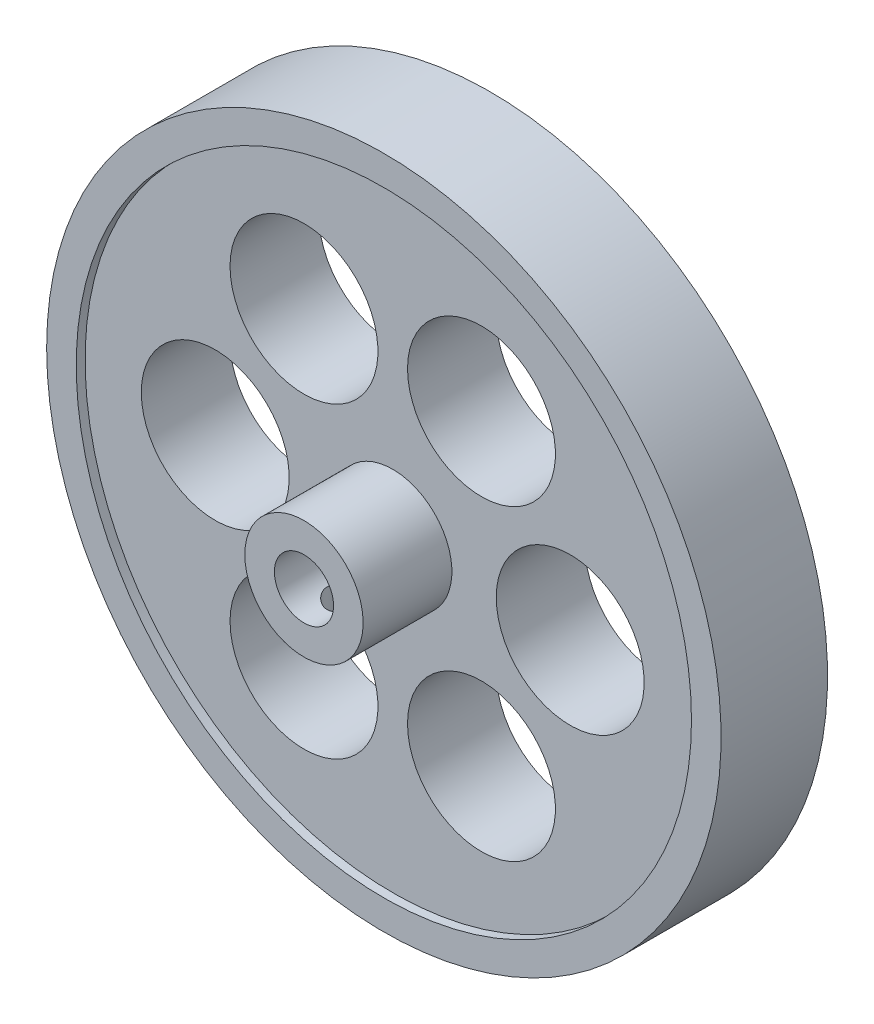
SolidWorks part; units mm, degrees
ref_plane "前视基准面" through (0, 0, 0) normal (0, 0, 1) x (1, 0, 0)
ref_plane "上视基准面" through (0, 0, 0) normal (0, 1, 0) x (1, 0, 0)
ref_plane "右视基准面" through (0, 0, 0) normal (1, 0, 0) x (0, 0, -1)
other "Configuration Table"
ref_plane "基准面1" through (0, 0, 0) normal (0, -1, 0) x (1, 0, 0)
sketch "草图1" plane through (0, 0, 0) normal (0, -1, 0) x (1, 0, 0)
  line L0 (57, 9) -> (0, 9)
  line L1 (0, 9) -> (0, -9)
  line L2 (0, -9) -> (57, -9)
  line L3 (57, -9) -> (57, 9)
  line L4 (0, 9) -> (0, -9) construction
revolve "旋转1" add sketch "草图1" angle 360 about L4
hole_wizard "M100 间隙孔1" positions "草图3" profile "草图2" hole size "M100" standard "ANSI Metric"
sketch "草图3" plane through (0, 0, 9) normal (0, 0, 1) x (1, 0, 0)
  point P0 (0, 0)
sketch "草图2" plane through (0, 0, 9) normal (1, 0, 0) x (0, -1, 0)
  line L0 (0, 0) -> (0, 1.5)
  line L1 (0, 1.5) -> (52, 1.5)
  line L2 (52, 1.5) -> (52, 0)
  line L5 (52, 0) -> (0, 0)
  line L10 (0, 1.5) -> (-52, 1.5) construction
  line L11 (0, -6.35) -> (0, 107.95) construction
  dimension "孔直径" = 104
  dimension "孔深度" = 1.5
  dimension "导头角度" = 180
sketch "草图4" plane through (0, 0, 0) normal (0, -1, 0) x (1, 0, 0)
  line L0 (10, 22.5) -> (0, 22.5)
  line L1 (0, 22.5) -> (0, 7.5)
  line L2 (0, 7.5) -> (10, 7.5)
  line L3 (10, 7.5) -> (10, 22.5)
  line L4 (0, 22.5) -> (0, 7.5) construction
revolve "旋转2" add sketch "草图4" angle 360 about L4
hole_wizard "M8 六角头螺栓的柱形沉头孔1" positions "草图6" profile "草图5" counterbore size "M8" standard "ANSI Metric"
sketch "草图6" plane through (0, 0, -9) normal (0, 0, -1) x (-1, 0, 0)
  point P0 (0, 0)
sketch "草图5" plane through (0, 0, -9) normal (1, 0, 0) x (0, 1, 0)
  line L0 (0, 0) -> (0, 31.5)
  line L1 (0, 31.5) -> (5, 31.5)
  line L3 (5, 31.5) -> (5, 1.5)
  line L4 (5, 1.5) -> (52, 1.5)
  line L5 (52, 1.5) -> (52, 0)
  line L7 (52, 0) -> (0, 0)
  line L11 (0, -6.35) -> (0, 107.95) construction
  dimension "通孔孔直径" = 10
  dimension "通孔孔深度" = 31.5
  dimension "柱形沉头孔直径" = 104
  dimension "柱形沉头孔深度" = 1.5
hole_wizard "Ø5.2 (5.2) 直径孔1" positions "3D草图1" profile "草图7" hole size "Ø5.2" standard "ANSI Metric"
sketch3d "3D草图1"
  point P0 (0, -10, 16)
sketch "草图7" plane through (0, -10, 16) normal (1, 0, 0) x (0, 0, -1)
  line L0 (0, 0) -> (0, 5)
  line L1 (0, 5) -> (2.6, 5)
  line L2 (2.6, 5) -> (2.6, 0)
  line L5 (2.6, 0) -> (0, 0)
  line L11 (0, -6.35) -> (0, 107.95) construction
  dimension "通孔孔直径" = 5.2
  dimension "通孔孔深度" = 5
hole_wizard "Ø25.0 (25) 直径孔1" positions "草图9" profile "草图8" hole size "Ø25.0" standard "ANSI Metric"
sketch "草图9" plane through (0, 0, -7.5) normal (0, 0, -1) x (-1, 0, 0)
  point P0 (-30, 0)
  point P1 (-15, 25.9808)
  point P2 (15, 25.9808)
  point P3 (30, 0)
  point P4 (15, -25.9808)
  point P5 (-15, -25.9808)
sketch "草图8" plane through (30, 0, -7.5) normal (1, 0, 0) x (0, 1, 0)
  line L0 (0, 0) -> (0, 30)
  line L1 (0, 30) -> (12.5, 30)
  line L2 (12.5, 30) -> (12.5, 0)
  line L5 (12.5, 0) -> (0, 0)
  line L11 (0, -6.35) -> (0, 107.95) construction
  dimension "通孔孔直径" = 25
  dimension "通孔孔深度" = 30
